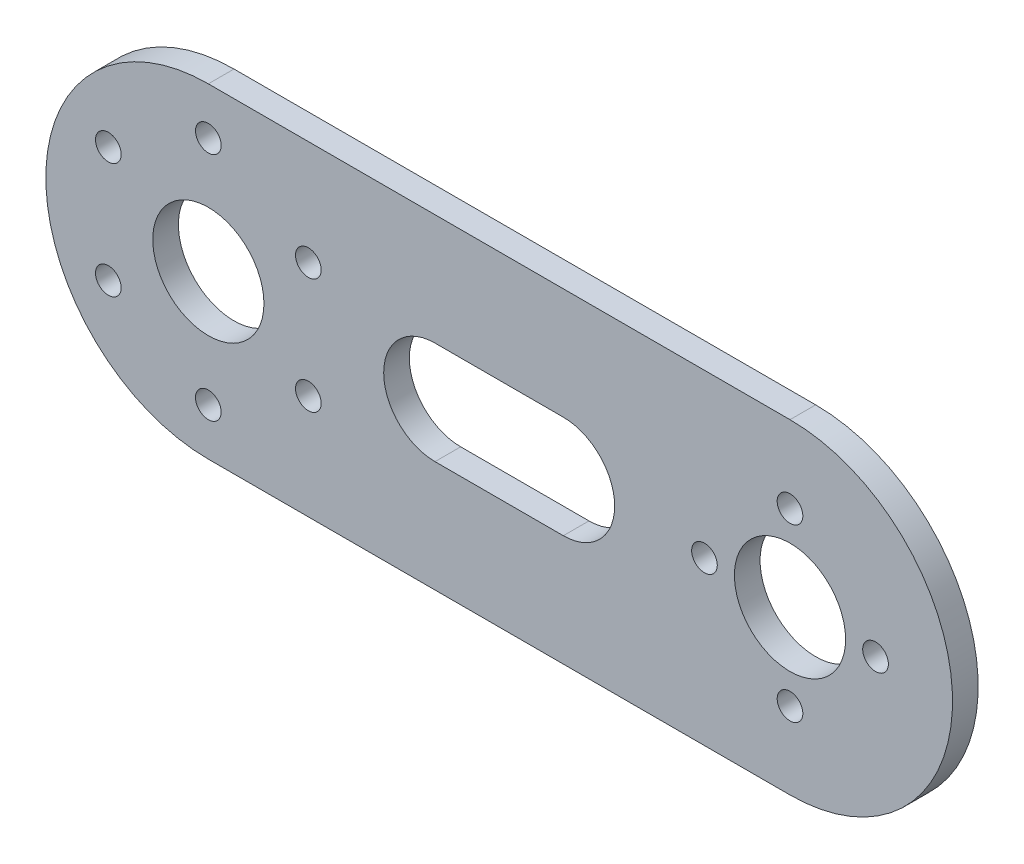
SolidWorks part; units mm, degrees
ref_plane "前视基准面" through (0, 0, 0) normal (0, 0, 1) x (1, 0, 0)
ref_plane "上视基准面" through (0, 0, 0) normal (0, 1, 0) x (1, 0, 0)
ref_plane "右视基准面" through (0, 0, 0) normal (1, 0, 0) x (0, 0, -1)
other "Configuration Table"
sketch "草图1" plane through (0, 0, 0) normal (0, 0, 1) x (1, 0, 0)
  line L0 (0, 19) -> (68, 19)
  line L1 (68, -19) -> (0, -19)
  circle A0 centre (0, 13.5) radius 1.5
  circle A1 centre (11.6913, 6.75) radius 1.5
  circle A2 centre (11.6913, -6.75) radius 1.5
  circle A3 centre (0, -13.5) radius 1.5
  circle A4 centre (-11.6913, -6.75) radius 1.5
  circle A5 centre (-11.6913, 6.75) radius 1.5
  circle A6 centre (0, 0) radius 6.5
  circle A7 centre (0, 0) radius 19
  circle A8 centre (68, 0) radius 6.5
  circle A9 centre (68, 10) radius 1.5
  circle A10 centre (78, 0) radius 1.5
  circle A11 centre (68, -10) radius 1.5
  circle A12 centre (58, 0) radius 1.5
  circle A13 centre (68, 0) radius 19
  point P15 (0, 0)
  point P30 (68, 0)
  dimension "D1" = 3
  dimension "D4" = 13
  dimension "D5" = 38
  dimension "D7" = 3
  dimension "D10" = 13
  dimension "D11" = 38
  dimension "D2" = 13.5
  dimension "D6" = 68
  dimension "D8" = 10
  dimension "D3" = 6
  dimension "D9" = 4
extrude "凸台-拉伸1" add sketch "草图1" along normal blind 3 contours A7 A0 A1 A2 A3 A4 A5 A6 | A13 L0 A7 L1 | A13 A8 A9 A10 A11 A12
sketch "草图2" plane through (0, 0, 3) normal (0, 0, 1) x (1, 0, 0)
  line L0 (0, 0) -> (68, 0) construction
  line L1 (26.5, 0) -> (41.5, 0) construction
  line L2 (26.5, 6) -> (41.5, 6)
  line L3 (26.5, -6) -> (41.5, -6)
  circle A0 centre (68, 0) radius 6.5 construction
  circle A1 centre (68, 0) radius 6.5
  arc A2 (26.5, 6) -> (26.5, -6) centre (26.5, 0) ccw
  arc A3 (41.5, -6) -> (41.5, 6) centre (41.5, 0) ccw
  point P7 (34, 0)
  dimension "D1" = 6
  dimension "D2" = 15
extrude "切除-拉伸1" cut sketch "草图2" against normal through all
